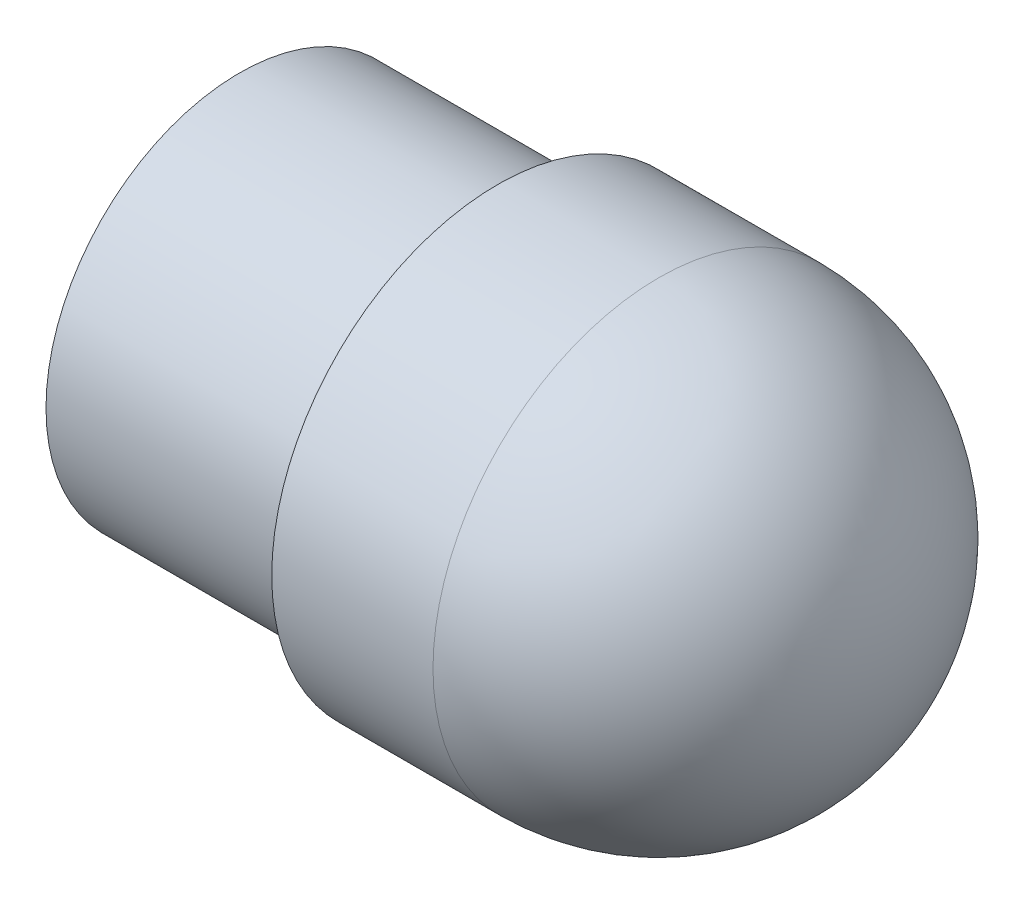
SolidWorks part; units mm, degrees
ref_plane "前基準面" through (0, 0, 0) normal (0, 0, 1) x (1, 0, 0)
ref_plane "上基準面" through (0, 0, 0) normal (0, 1, 0) x (1, 0, 0)
ref_plane "右基準面" through (0, 0, 0) normal (1, 0, 0) x (0, 0, -1)
ref_plane "平面1"
sketch "草圖1" plane through (0, 0, 0) normal (0, 0, 1) x (1, 0, 0)
  line L0 (20, 0) -> (32.5, 0)
  line L1 (32.5, 0) -> (32.5, 17.5)
  line L2 (32.5, 17.5) -> (20, 17.5)
  line L3 (20, 17.5) -> (20, 0)
  line L4 (0, 0) -> (20, 0) construction
  line L5 (32.5, 17.5) -> (32.5, 0)
  line L6 (32.5, 0) -> (50, 0)
  line L7 (0, 0) -> (20, 0)
  line L8 (20, 0) -> (20, 15)
  line L9 (20, 15) -> (0, 15)
  line L10 (0, 15) -> (0, 0)
  arc A0 (50, 0) -> (32.5, 17.5) centre (32.5, 0) ccw
  dimension "D1" = 20
  dimension "D2" = 15
  dimension "D3" = 12.5
  dimension "D4" = 17.5
revolve "迴轉1" add sketch "草圖1" angle 360 about L4
